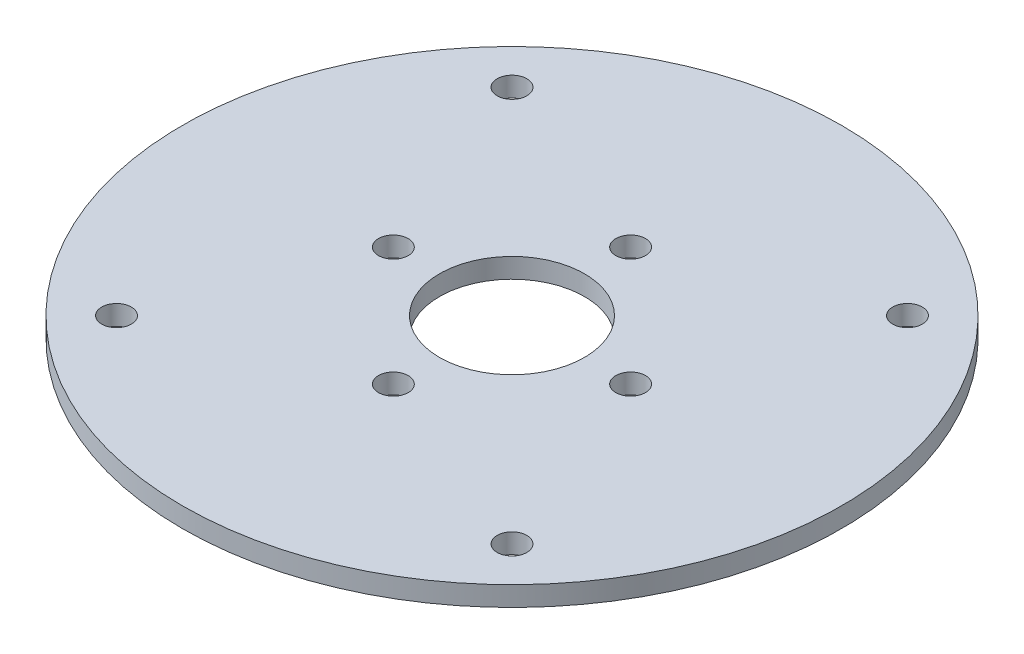
SolidWorks part; units mm, degrees
ref_plane "前视基准面" through (0, 0, 0) normal (0, 0, 1) x (1, 0, 0)
ref_plane "上视基准面" through (0, 0, 0) normal (0, 1, 0) x (1, 0, 0)
ref_plane "右视基准面" through (0, 0, 0) normal (1, 0, 0) x (0, 0, -1)
sketch "草图1" plane through (0, 0, 0) normal (0, 1, 0) x (1, 0, 0)
  circle A0 centre (0, 0) radius 50
  dimension "D1" = 100
extrude "凸台-拉伸2" add sketch "草图1" along normal blind 3 contours A0
sketch "草图3" plane through (0, 0, 0) normal (0, 1, 0) x (1, 0, 0)
  line L0 (0, 0) -> (-50, 0) construction
  line L1 (0, 0) -> (0, 50) construction
  line L2 (-18, 0) -> (-18, 50)
  line L3 (-27.8319, 18) -> (8.9222, 18)
  line L4 (-30, 0) -> (-30, 39.0179)
  line L5 (53.6663, 30) -> (-53.6663, 30)
  circle A0 centre (0, 0) radius 50 construction
  circle A1 centre (-18, 0) radius 2.25
  circle A2 centre (-30, 30) radius 2.25
  circle A5 centre (30, 30) radius 2.25
  circle A6 centre (30, -30) radius 2.25
  circle A7 centre (-30, -30) radius 2.25
  circle A8 centre (30, 30) radius 2.25
  circle A9 centre (0, 18) radius 2.25
  circle A10 centre (30, -30) radius 2.25
  circle A11 centre (18, 0) radius 2.25
  circle A12 centre (-30, -30) radius 2.25
  circle A13 centre (0, -18) radius 2.25
  point P19 (0, 30)
  point P28 (0, 0)
  point P41 (0, 0)
  dimension "D3" = 30
  dimension "D5" = 4
  dimension "D1" = 18
  dimension "D2" = 18
  dimension "D4" = 30
  dimension "D6" = 4
extrude "切除-拉伸1" cut sketch "草图3" along normal through all contours A1 | A6 | A7 | A9 | A5 | A2 | A13 | A11
sketch "草图4" plane through (0, 0, 0) normal (0, 1, 0) x (1, 0, 0)
  circle A0 centre (0, 0) radius 11
extrude "切除-拉伸2" cut sketch "草图4" along normal through all contours A0
